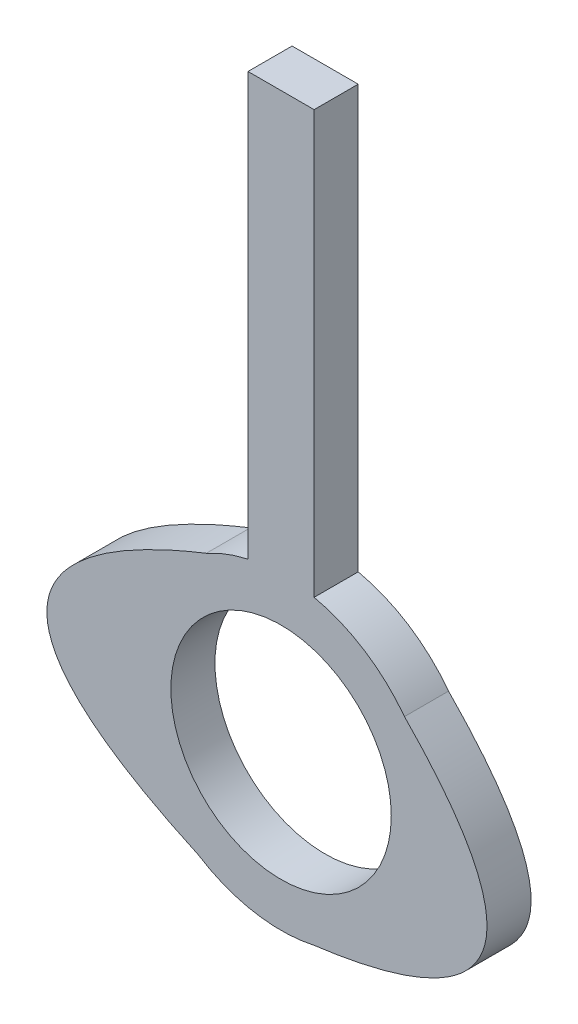
SolidWorks part; units mm, degrees
ref_plane "Front Plane" through (0, 0, 0) normal (0, 0, 1) x (1, 0, 0)
ref_plane "Top Plane" through (0, 0, 0) normal (0, 1, 0) x (1, 0, 0)
ref_plane "Right Plane" through (0, 0, 0) normal (1, 0, 0) x (0, 0, -1)
sketch "Sketch1" plane through (0, 0, 0) normal (0, 0, 1) x (1, 0, 0)
  line L0 (-1.5, 6.8374) -> (-1.5, 26)
  line L1 (-1.5, 26) -> (1.5, 26)
  line L2 (0, -55) -> (0, 55) construction
  line L3 (1.5, 6.8374) -> (1.5, 26)
  circle A0 centre (0, 0) radius 5
  arc A1 (-1.5, 6.8374) -> (1.5, 6.8374) centre (0, 0) ccw
  point P10 (0, 26)
  dimension "D1" = 10
  dimension "D2" = 14
  dimension "D3" = 26
  dimension "D4" = 1.5
extrude "Boss-Extrude1" add sketch "Sketch1" along normal blind 2
sketch "Sketch2" plane through (0, 0, 0) normal (0, 0, -1) x (-1, 0, 0)
  arc A0 (-1.5, 6.8374) -> (1.5, 6.8374) centre (0, 0) ccw construction
  spline S0 degree 2 poles (-5.5993, 4.201) (-15.258, -5.6281) (0, -7) knots 0 0 0 1 1 1
  spline S1 degree 2 poles (3.3936, 6.1224) (18.6682, 0.0497) (1.6775, -6.796) knots 0 0 0 1 1 1
  spline S2 degree 2 poles (3.3936, 6.1224) (10.1242, -1.4143) (1.6775, -6.796) knots 0 0 0 1 1 1
  spline S3 degree 2 poles (-5.5993, 4.201) (-7.9816, -4.5358) (0, -7) knots 0 0 0 1 1 1
extrude "Boss-Extrude2" add sketch "Sketch2" against normal up to surface (2 mm away) up to face at (0, 12.9593, 2)
